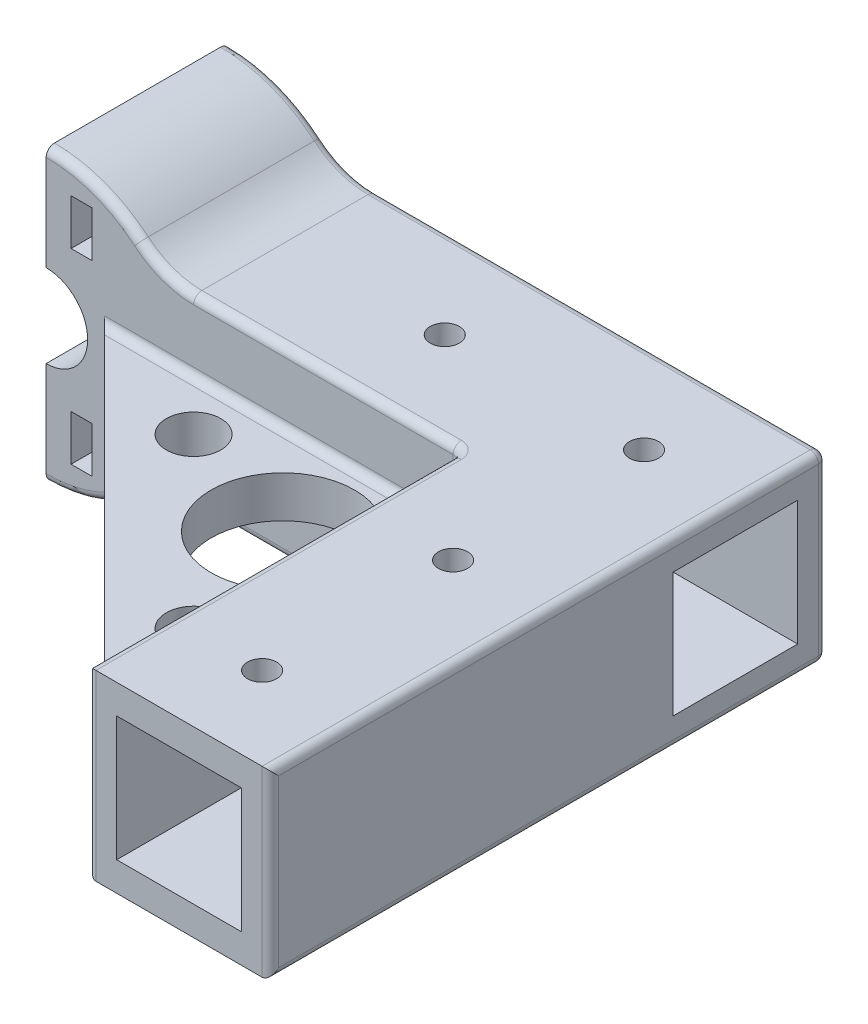
SolidWorks part; units mm, degrees
ref_plane "Front Plane" through (0, 0, 0) normal (0, 0, 1) x (1, 0, 0)
ref_plane "Top Plane" through (0, 0, 0) normal (0, 1, 0) x (1, 0, 0)
ref_plane "Right Plane" through (0, 0, 0) normal (1, 0, 0) x (0, 0, -1)
sketch "Sketch1" plane through (0, 0, 0) normal (0, 0, 1) x (1, 0, 0)
  line L0 (41.5599, 4.1233) -> (41.5599, -17.8767) construction
  line L1 (5.1706, 4.1233) -> (63.5599, 4.1233)
  line L2 (-8.4401, 7.6443) -> (-8.4401, -1.8767)
  line L3 (5.1706, -17.8767) -> (63.5599, -17.8767)
  line L4 (63.5599, 4.1233) -> (63.5599, -17.8767)
  line L5 (-8.4401, -11.8767) -> (-8.4401, -14.3557)
  line L6 (-8.4401, -14.3557) -> (-8.4401, -24.3767)
  line L7 (-8.4401, 7.6443) -> (-8.4401, 10.6233)
  arc A0 (-8.4401, -11.8767) -> (-8.4401, -1.8767) centre (-8.4401, -6.8767) ccw
  arc A1 (5.1706, 4.1233) -> (-8.4401, 10.6233) centre (-8.4401, -6.8767) ccw
  arc A2 (-8.4401, -24.3767) -> (5.1706, -17.8767) centre (-8.4401, -6.8767) ccw
  dimension "D4" = 10
  dimension "D5" = 35
  dimension "D1" = 22
  dimension "D2" = 50
  dimension "D3" = 22
  dimension "D6" = 11
extrude "Boss-Extrude1" add sketch "Sketch1" along normal blind 22
sketch "Sketch2" plane through (0, 0, 22) normal (0, 0, 1) x (1, 0, 0)
  line L0 (5.1706, -17.8767) -> (63.5599, -17.8767) construction
  line L1 (63.5599, 4.1233) -> (41.5599, 4.1233)
  line L2 (63.5599, 4.1233) -> (63.5599, -17.8767)
  line L3 (63.5599, -17.8767) -> (41.5599, -17.8767)
  line L4 (41.5599, 4.1233) -> (41.5599, -17.8767)
  dimension "D1" = 22
extrude "Boss-Extrude2" add sketch "Sketch2" along normal blind 45
sketch "Sketch3" plane through (0, 0, 67) normal (0, 0, 1) x (1, 0, 0)
  line L0 (63.5599, -17.8767) -> (63.5599, 4.1233) construction
  line L1 (45.0599, 0.6233) -> (60.0599, 0.6233)
  line L2 (45.0599, 0.6233) -> (45.0599, -14.3767)
  line L3 (45.0599, -14.3767) -> (60.0599, -14.3767)
  line L4 (60.0599, 0.6233) -> (60.0599, -14.3767)
  line L5 (63.5599, 4.1233) -> (41.5599, 4.1233) construction
  dimension "D1" = 15
  dimension "D2" = 3.5
  dimension "D3" = 15
  dimension "D4" = 3.5
extrude "Cut-Extrude1" cut sketch "Sketch3" against normal offset from surface (43 mm away) 2 up to face at (8.2716, -5.5017, 22)
sketch "Sketch4" plane through (63.5599, 0, 0) normal (1, 0, 0) x (0, 0, -1)
  line L0 (-67, 4.1233) -> (0, 4.1233) construction
  line L1 (-3.5, 0.6233) -> (-18.5, 0.6233)
  line L2 (-3.5, 0.6233) -> (-3.5, -14.3767)
  line L3 (-3.5, -14.3767) -> (-18.5, -14.3767)
  line L4 (-18.5, 0.6233) -> (-18.5, -14.3767)
  line L5 (0, -17.8767) -> (0, 4.1233) construction
  dimension "D1" = 15
  dimension "D2" = 15
  dimension "D3" = 3.5
  dimension "D4" = 3.5
extrude "Cut-Extrude2" cut sketch "Sketch4" against normal blind 45
ref_plane "Plane1" through (0, -6.8767, 0) normal (0, 1, 0) x (1, 0, 0)
sketch "Sketch6" plane through (0, -6.8767, 0) normal (0, 1, 0) x (1, 0, 0)
  line L0 (-1.4401, -22) -> (41.5599, -65)
  line L1 (41.5599, -22) -> (5.1706, -22) construction
  line L2 (41.5599, -67) -> (41.5599, -22) construction
  line L3 (41.5599, -65) -> (41.5599, -22)
  line L4 (41.5599, -22) -> (-1.4401, -22)
  line L5 (-3.4401, -22) -> (-3.4401, 0) construction
  dimension "D1" = 2
  dimension "D2" = 45
extrude "Boss-Extrude3" add sketch "Sketch6" along normal blind 2.5 and the other way blind 2.5
fillet "Fillet1" radius 10 2 edges at (5.1706, -17.8767, 11) (5.1706, 4.1233, 11)
sketch "Sketch5" plane through (-8.4401, 0, 0) normal (-1, 0, 0) x (0, 0, 1)
  line L0 (0, 4.3733) -> (22, 4.3733) construction
  line L1 (0, 10.6233) -> (0, -1.8767) construction
  line L2 (22, 10.6233) -> (22, -1.8767) construction
  line L3 (0, -18.1267) -> (22, -18.1267) construction
  line L4 (0, -11.8767) -> (0, -24.3767) construction
  line L5 (22, -11.8767) -> (22, -24.3767) construction
  circle A1 centre (11, 4.3733) radius 1.75
  circle A3 centre (11, -18.1267) radius 1.75
  dimension "D1" = 3.5
  dimension "D4" = 11
  dimension "D5" = 11
extrude "Cut-Extrude3" cut sketch "Sketch5" against normal blind 8
sketch "Sketch8" plane through (0, -17.8767, 0) normal (0, -1, 0) x (1, 0, 0)
  line L0 (18.5599, 11) -> (63.5599, 11) construction
  line L1 (18.5599, 18.5) -> (18.5599, 3.5) construction
  line L2 (63.5599, 67) -> (63.5599, 0) construction
  line L3 (52.5599, 24) -> (52.5599, 67) construction
  line L4 (60.0599, 24) -> (45.0599, 24) construction
  line L5 (41.5599, 67) -> (63.5599, 67) construction
  circle A0 centre (28.5599, 11) radius 1.75
  circle A1 centre (52.5599, 11) radius 1.75
  circle A2 centre (52.5599, 34) radius 1.75
  circle A3 centre (52.5599, 57) radius 1.75
  dimension "D1" = 3.5
  dimension "D2" = 10
  dimension "D3" = 10
  dimension "D4" = 10
extrude "Cut-Extrude5" cut sketch "Sketch8" against normal up to surface (22 mm away)
sketch "Sketch9" plane through (0, 0, 0) normal (0, 0, -1) x (-1, 0, 0)
  line L0 (-61.5599, -12.8767) -> (-9.3152, -12.8767) construction
  line L2 (-9.3152, -17.8767) -> (-63.5599, -17.8767) construction
  line L3 (-63.5599, -17.8767) -> (-63.5599, 4.1233) construction
  text T0 "ALFR3D" font "Murder Of Mayday" height 12
  dimension "D1" = 5
  dimension "D2" = 2
extrude "Cut-Extrude6" cut sketch "Sketch9" against normal blind 1.5
sketch "Sketch10" plane through (0, -9.3767, 0) normal (0, -1, 0) x (1, 0, 0)
  line L0 (41.5599, 22) -> (20.0599, 43.5) construction
  line L1 (-1.4401, 22) -> (41.5599, 65) construction
  line L2 (41.5599, 67) -> (41.5599, 22) construction
  line L3 (41.5599, 22) -> (-1.4401, 22) construction
  circle A0 centre (30.8099, 32.75) radius 8.6369
  circle A1 centre (35.5599, 48.25) radius 3.2807
  circle A2 centre (15.3099, 28) radius 3.2807
  dimension "D1" = 6
  dimension "D2" = 6
  dimension "D3" = 15.5
  dimension "D4" = 15.5
extrude "Cut-Extrude7" cut sketch "Sketch10" against normal up to surface (5 mm away) up to face at (27.2266, -4.3767, 36.3333)
fillet "Fillet2" radius 1 25 edges at (-2.424, 9.5567, 22) (5.8774, 4.7328, 22) (-2.424, -23.3101, 22) (5.8774, -18.4862, 22) (-2.424, -23.3101, 0) (5.8774, -18.4862, 0) (-2.424, 9.5567, 0) (5.8774, 4.7328, 0) (41.5599, -6.8767, 67) (63.5599, -6.8767, 67) (20.0599, -9.3767, 22) (41.5599, -9.3767, 43.5) (20.0599, -4.3767, 22) (41.5599, -4.3767, 43.5) (63.5599, 4.1233, 33.5) (63.5599, -17.8767, 33.5) (63.5599, -6.8767, 0) (36.4376, -17.8767, 0) (36.4376, 4.1233, 0)
sketch "Sketch11" plane through (0, 0, 22) normal (0, 0, 1) x (1, 0, 0)
  line L0 (-0.4401, 4.3733) -> (-8.4401, 4.3733) construction
  line L1 (-0.4401, 6.1233) -> (-0.4401, 2.6233) construction
  line L2 (-8.4401, 9.6233) -> (-8.4401, -1.8767) construction
  line L3 (-0.4401, -18.1267) -> (-8.4401, -18.1267) construction
  line L4 (-0.4401, -16.3767) -> (-0.4401, -19.8767) construction
  line L5 (-8.4401, -11.8767) -> (-8.4401, -23.3767) construction
  line L7 (-5.4401, 7.1233) -> (-2.9401, 7.1233)
  line L8 (-5.4401, 7.1233) -> (-5.4401, 1.6233)
  line L9 (-5.4401, 1.6233) -> (-2.9401, 1.6233)
  line L10 (-2.9401, 7.1233) -> (-2.9401, 1.6233)
  line L11 (-5.4401, -15.3767) -> (-2.9401, -15.3767)
  line L12 (-5.4401, -15.3767) -> (-5.4401, -20.8767)
  line L13 (-5.4401, -20.8767) -> (-2.9401, -20.8767)
  line L14 (-2.9401, -15.3767) -> (-2.9401, -20.8767)
  dimension "D1" = 5.5
  dimension "D2" = 2.75
  dimension "D3" = 2.75
  dimension "D4" = 3
  dimension "D5" = 2.5
extrude "Cut-Extrude8" cut sketch "Sketch11" against normal blind 12
sketch "Sketch12" plane through (-2.9401, 0, 0) normal (-1, 0, 0) x (0, 0, 1)
  line L1 (10, -15.3767) -> (22, -15.3767) construction
  line L2 (8.9123, -20.8767) -> (12.0877, -20.8767)
  line L3 (12.0877, -20.8767) -> (13.6754, -18.1267)
  line L4 (13.6754, -18.1267) -> (12.0877, -15.3767)
  line L5 (12.0877, -15.3767) -> (8.9123, -15.3767)
  line L6 (8.9123, -15.3767) -> (7.3246, -18.1267)
  line L7 (7.3246, -18.1267) -> (8.9123, -20.8767)
  line L8 (10, 7.1233) -> (22, 7.1233) construction
  line L9 (12.0877, 7.1233) -> (8.9123, 7.1233)
  line L10 (8.9123, 7.1233) -> (7.3246, 4.3733)
  line L11 (7.3246, 4.3733) -> (8.9123, 1.6233)
  line L12 (8.9123, 1.6233) -> (12.0877, 1.6233)
  line L13 (12.0877, 1.6233) -> (13.6754, 4.3733)
  line L14 (13.6754, 4.3733) -> (12.0877, 7.1233)
  circle A0 centre (10.5, -18.1267) radius 2.75 construction
  circle A1 centre (10.5, 4.3733) radius 2.75 construction
  circle A2 centre (11, 4.3733) radius 1.75 construction
  dimension "D1" = 5.5
  dimension "D2" = 0.5
  dimension "D3" = 5.5
extrude "Cut-Extrude9" cut sketch "Sketch12" along normal up to surface (2.5 mm away) up to face at (-5.4401, 4.3733, 14.4583)
